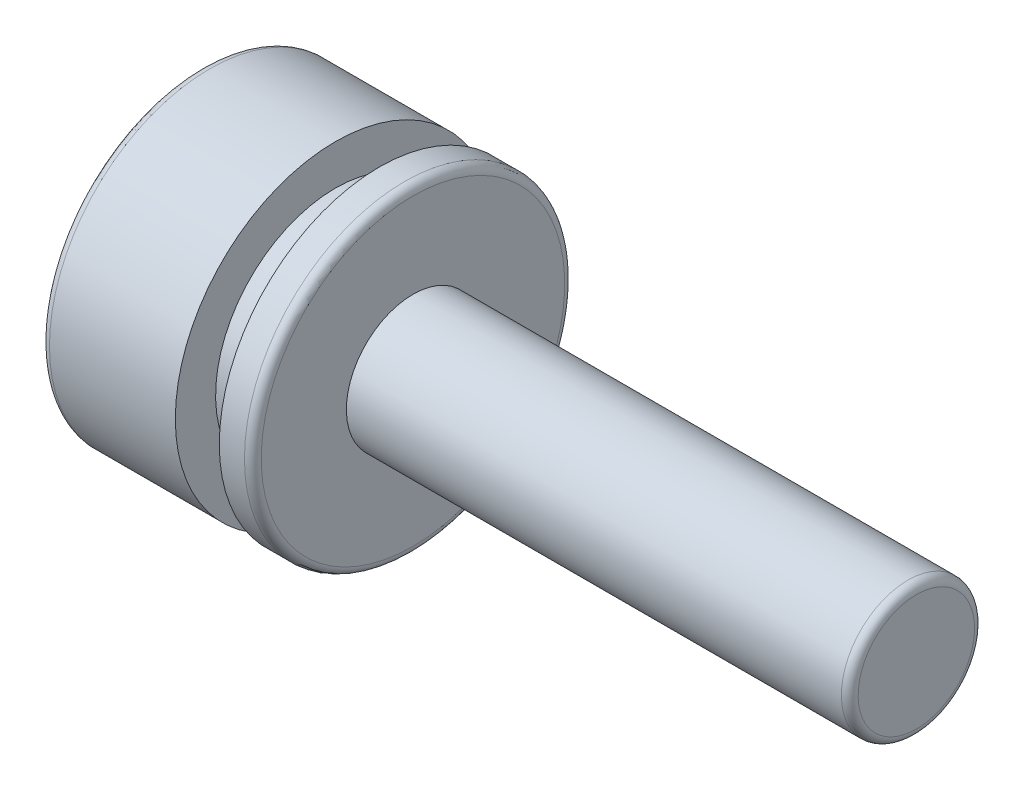
SolidWorks part; units mm, degrees
material "Cobre"
ref_plane "Plano frontal" through (0, 0, 0) normal (0, 0, 1) x (1, 0, 0)
ref_plane "Plano superior" through (0, 0, 0) normal (0, 1, 0) x (1, 0, 0)
ref_plane "Plano direito" through (0, 0, 0) normal (1, 0, 0) x (0, 0, -1)
sketch "Esboço1" plane through (0, 0, 0) normal (0, 0, 1) x (1, 0, 0)
  line L0 (0, 5) -> (0, 9.5438)
  line L1 (0, 9.5438) -> (8, 9.5438)
  line L2 (8, 9.5438) -> (8, 7.1438)
  line L3 (8, 7.1438) -> (10.62, 7.1438)
  line L4 (10.62, 7.1438) -> (10.62, 9.5438)
  line L5 (10.62, 9.5438) -> (12.62, 9.5438)
  line L6 (12.62, 9.5438) -> (12.62, 3.9688)
  line L7 (12.62, 3.9688) -> (42.62, 3.9688)
  line L8 (42.62, 3.9688) -> (42.62, 0)
  line L9 (42.62, 0) -> (9.3868, 0)
  line L10 (6.5, 5) -> (9.3868, 0)
  line L11 (6.5, 5) -> (0, 5)
  line L12 (17.62, -983.4398) -> (17.62, 49016.5602) construction
  line L13 (5.62, -1013.9319) -> (5.62, 48986.0681) construction
  dimension "D2" = 7.1437
  dimension "D3" = 2.62
  dimension "D4" = 2.4
  dimension "D5" = 2.4
  dimension "D6" = 6.5
  dimension "D7" = 8
  dimension "D8" = 2
  dimension "D9" = 30
  dimension "D10" = 3.9688
  dimension "D11" = 60
  dimension "D12" = 12
  dimension "D13" = 5
  dimension "D14" = 9.5437
  dimension "D15" = 5
revolve "Revolução1" add sketch "Esboço1" angle 360 about L9
cosmetic thread "Representação de rosca1" parameters "D2"=6.2586
cosmetic thread "Representação de rosca2" parameters "D2"=11.1125
fillet "Filete1" radius 0.5 1 edges at (42.62, 3.9688, 0)
fillet "Filete2" radius 0.5 1 edges at (0, 5, 0)
fillet "Filete3" radius 0.5 1 edges at (0, 9.5438, 0)
fillet "Filete4" radius 0.5 1 edges at (12.62, 9.5438, 0)
